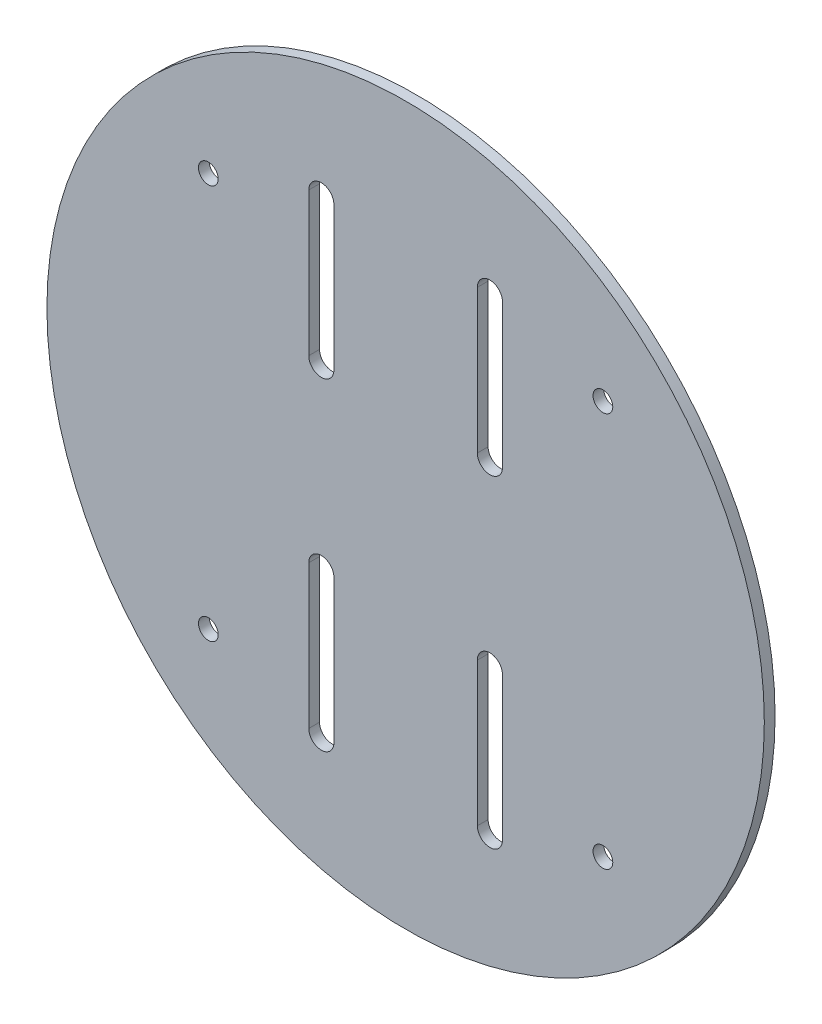
SolidWorks part; units mm, degrees
ref_plane "Ön Düzlem" through (0, 0, 0) normal (0, 0, 1) x (1, 0, 0)
ref_plane "Üst Düzlem" through (0, 0, 0) normal (0, 1, 0) x (1, 0, 0)
ref_plane "Sağ Düzlem" through (0, 0, 0) normal (1, 0, 0) x (0, 0, -1)
sketch "Çizim1" plane through (0, 0, 0) normal (0, 0, 1) x (1, 0, 0)
  circle A0 centre (0, 0) radius 100
  dimension "D1" = 200
extrude "Yükseklik-Ekstrüzyon1" add sketch "Çizim1" along normal blind 30
sketch "Çizim9" plane through (0, 0, 30) normal (0, 0, 1) x (1, 0, 0)
  line L0 (23.5, 65) -> (23.5, 25) construction
  line L1 (27, 65) -> (27, 25)
  line L2 (20, 65) -> (20, 25)
  line L3 (-23.5, 65) -> (-23.5, 25) construction
  line L4 (-20, 65) -> (-20, 25)
  line L5 (-27, 65) -> (-27, 25)
  line L6 (-23.5, -25) -> (-23.5, -65) construction
  line L7 (-20, -25) -> (-20, -65)
  line L8 (-27, -25) -> (-27, -65)
  line L9 (23.5, -65) -> (23.5, -25) construction
  line L10 (20, -65) -> (20, -25)
  line L11 (27, -65) -> (27, -25)
  arc A0 (27, 65) -> (20, 65) centre (23.5, 65) ccw
  arc A1 (20, 25) -> (27, 25) centre (23.5, 25) ccw
  arc A2 (-20, 65) -> (-27, 65) centre (-23.5, 65) ccw
  arc A3 (-27, 25) -> (-20, 25) centre (-23.5, 25) ccw
  arc A4 (-20, -25) -> (-27, -25) centre (-23.5, -25) ccw
  arc A5 (-27, -65) -> (-20, -65) centre (-23.5, -65) ccw
  arc A6 (20, -65) -> (27, -65) centre (23.5, -65) ccw
  arc A7 (27, -25) -> (20, -25) centre (23.5, -25) ccw
  circle A8 centre (0, -55) radius 2.6 construction
  circle A9 centre (0, 0) radius 100 construction
  point P2 (23.5, 45)
  point P8 (-23.5, 45)
  point P15 (-23.5, -45)
  point P22 (23.5, -45)
  dimension "D2" = 40
  dimension "D11" = 50
  dimension "D13" = 65
  dimension "D1" = 7
  dimension "D3" = 40
  dimension "D4" = 7
  dimension "D5" = 7
  dimension "D6" = 40
  dimension "D7" = 40
  dimension "D8" = 7
  dimension "D9" = 40
  dimension "D10" = 50
  dimension "D12" = 20
  dimension "D14" = 65
extrude "Kes-Ekstrüzyon1" cut sketch "Çizim9" against normal through all
hole_wizard "M5 Boşluklu Delik2" positions "Çizim19" profile "Çizim18" hole size "M5" standard "ANSI Metrik" end condition through all
sketch "Çizim19" plane through (0, 0, 30) normal (0, 0, 1) x (1, 0, 0)
  point P0 (-55, 55)
  point P2 (55, 55)
  point P4 (55, -55)
  point P6 (-55, -55)
sketch "Çizim18" plane through (-55, 55, 30) normal (1, 0, 0) x (0, -1, 0)
  line L0 (0, 0) -> (0, 30)
  line L1 (0, 30) -> (2.75, 30)
  line L2 (2.75, 30) -> (2.75, 0)
  line L5 (2.75, 0) -> (0, 0)
  line L11 (0, -6.35) -> (0, 107.95) construction
  dimension "Thru Hole Dia." = 5.5
  dimension "Thru Hole Depth" = 30
sketch "Çizim20" plane through (0, 0, 30) normal (0, 0, 1) x (1, 0, 0)
  circle A0 centre (0, 8.4795) radius 183.5376
extrude "Kes-Ekstrüzyon3" cut sketch "Çizim20" against normal blind 27
